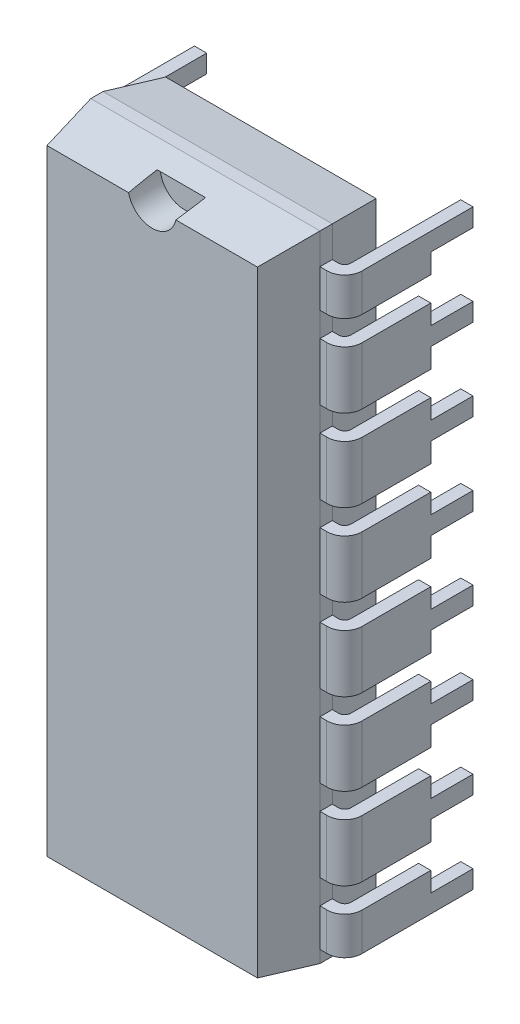
SolidWorks part; units mm, degrees
ref_plane "Спереди" through (0, 0, 0) normal (0, 0, 1) x (1, 0, 0)
ref_plane "Сверху" through (0, 0, 0) normal (0, 1, 0) x (1, 0, 0)
ref_plane "Справа" through (0, 0, 0) normal (1, 0, 0) x (0, 0, -1)
sketch "Эскиз1" plane through (0, 0, 0) normal (0, 0, 1) x (1, 0, 0)
  line L1 (-0.19, 0.28) -> (0.19, 0.28)
  line L2 (-0.19, 0.28) -> (-0.19, -0.89)
  line L3 (-0.19, -0.89) -> (0.19, -0.89)
  line L4 (0.19, 0.28) -> (0.19, -0.89)
  line L8 (-0.19, -1.65) -> (0.19, -1.65)
  line L9 (-0.19, -1.65) -> (-0.19, -3.43)
  line L10 (-0.19, -3.43) -> (0.19, -3.43)
  line L11 (0.19, -1.65) -> (0.19, -3.43)
  line L16 (-0.19, -4.19) -> (0.19, -4.19)
  line L17 (-0.19, -4.19) -> (-0.19, -5.97)
  line L18 (-0.19, -5.97) -> (0.19, -5.97)
  line L19 (0.19, -4.19) -> (0.19, -5.97)
  line L24 (-0.19, -6.73) -> (0.19, -6.73)
  line L25 (-0.19, -6.73) -> (-0.19, -8.51)
  line L26 (-0.19, -8.51) -> (0.19, -8.51)
  line L27 (0.19, -6.73) -> (0.19, -8.51)
  line L32 (-0.19, -9.27) -> (0.19, -9.27)
  line L33 (-0.19, -9.27) -> (-0.19, -11.05)
  line L34 (-0.19, -11.05) -> (0.19, -11.05)
  line L35 (0.19, -9.27) -> (0.19, -11.05)
  line L40 (-0.19, -11.81) -> (0.19, -11.81)
  line L41 (-0.19, -11.81) -> (-0.19, -13.59)
  line L42 (-0.19, -13.59) -> (0.19, -13.59)
  line L43 (0.19, -11.81) -> (0.19, -13.59)
  line L48 (-0.19, -14.35) -> (0.19, -14.35)
  line L49 (-0.19, -14.35) -> (-0.19, -16.13)
  line L50 (-0.19, -16.13) -> (0.19, -16.13)
  line L51 (0.19, -14.35) -> (0.19, -16.13)
  line L55 (-0.19, -16.89) -> (0.19, -16.89)
  line L57 (-0.19, -16.89) -> (-0.19, -18.06)
  line L58 (-0.19, -18.06) -> (0.19, -18.06)
  line L59 (0.19, -16.89) -> (0.19, -18.06)
ref_plane "Плоскость1" through (0, 0, 4.32) normal (0, 0, 1) x (1, 0, 0)
sketch "Эскиз2" plane through (0, 0, 4.32) normal (0, 0, 1) x (1, 0, 0)
  line L0 (4.13, 1.24) -> (4.13, -12.1874) construction
  line L1 (0.575, -8.6) -> (7.685, -8.6) construction
  line L7 (0.575, 1.24) -> (7.685, 1.24)
  line L8 (0.575, 1.24) -> (0.575, -18.44)
  line L9 (0.575, -18.44) -> (7.685, -18.44)
  line L10 (7.685, 1.24) -> (7.685, -18.44)
  dimension "D1" = 7.11
  dimension "D2" = 19.68
extrude "Вытянуть1" add sketch "Эскиз2" against normal blind 3.68
chamfer "Фаска1" distance 1.65 angle 10 8 edges at (4.13, -18.44, 0.64) (0.575, -8.6, 0.64) (4.13, 1.24, 0.64) (7.685, -8.6, 0.64) (4.13, -18.44, 4.32) (0.575, -8.6, 4.32) (4.13, 1.24, 4.32) (7.685, -8.6, 4.32)
sketch "Эскиз3" plane through (0, 0, 0) normal (0, 1, 0) x (1, 0, 0)
  line L0 (0, 0) -> (0, -2.1333)
  line L1 (0.3729, -2.4825) -> (4.1327, -2.4825)
  line L3 (4.13, -0.0853) -> (4.13, -2.9789) construction
  line L5 (7.8871, -2.4825) -> (4.1327, -2.4825)
  line L6 (8.26, 0) -> (8.26, -2.1333)
  arc A0 (0, -2.1333) -> (0.3729, -2.4825) centre (0.35, -2.1333) ccw
  arc A1 (8.26, -2.1333) -> (7.8871, -2.4825) centre (7.91, -2.1333) cw
  dimension "D2" = 0.35
  dimension "D1" = 8.26
  dimension "D3" = 2.4825
sweep "По траектории3" add profiles "Эскиз1" path "Эскиз3"
sketch "Эскиз4" plane through (0, 0, 0) normal (0, 0, 1) x (1, 0, 0)
  line L1 (8.07, 0.28) -> (8.45, 0.28)
  line L2 (8.07, 0.28) -> (8.07, -0.89)
  line L3 (8.07, -0.89) -> (8.45, -0.89)
  line L4 (8.45, 0.28) -> (8.45, -0.89)
  line L5 (8.07, -16.89) -> (8.45, -16.89)
  line L6 (8.07, -16.89) -> (8.07, -18.06)
  line L7 (8.07, -18.06) -> (8.45, -18.06)
  line L8 (8.45, -16.89) -> (8.45, -18.06)
  line L9 (8.07, -1.65) -> (8.45, -1.65)
  line L10 (8.07, -1.65) -> (8.07, -3.43)
  line L11 (8.07, -3.43) -> (8.45, -3.43)
  line L12 (8.45, -1.65) -> (8.45, -3.43)
  line L13 (8.07, -4.19) -> (8.45, -4.19)
  line L14 (8.07, -4.19) -> (8.07, -5.97)
  line L15 (8.07, -5.97) -> (8.45, -5.97)
  line L16 (8.45, -4.19) -> (8.45, -5.97)
  line L17 (8.07, -6.73) -> (8.45, -6.73)
  line L18 (8.07, -6.73) -> (8.07, -8.51)
  line L19 (8.07, -8.51) -> (8.45, -8.51)
  line L20 (8.45, -6.73) -> (8.45, -8.51)
  line L21 (8.07, -9.27) -> (8.45, -9.27)
  line L22 (8.07, -9.27) -> (8.07, -11.05)
  line L23 (8.07, -11.05) -> (8.45, -11.05)
  line L24 (8.45, -9.27) -> (8.45, -11.05)
  line L25 (8.07, -11.81) -> (8.45, -11.81)
  line L26 (8.07, -11.81) -> (8.07, -13.59)
  line L27 (8.07, -13.59) -> (8.45, -13.59)
  line L28 (8.45, -11.81) -> (8.45, -13.59)
  line L29 (8.07, -14.35) -> (8.45, -14.35)
  line L30 (8.07, -14.35) -> (8.07, -16.13)
  line L31 (8.07, -16.13) -> (8.45, -16.13)
  line L32 (8.45, -14.35) -> (8.45, -16.13)
sketch "Эскиз5" plane through (0, 0, 0) normal (0, 1, 0) x (1, 0, 0)
  line L0 (7.685, -2.48) -> (7.8737, -2.48)
  line L1 (7.685, -2.29) -> (7.685, -2.67) construction
  line L2 (8.26, -2.0937) -> (8.26, 0)
  line L3 (8.07, 0) -> (8.45, 0) construction
  arc A0 (7.8737, -2.48) -> (8.26, -2.0937) centre (7.8737, -2.0937) ccw
sweep "По траектории4" add profiles "Эскиз4" path "Эскиз5"
sketch "Эскиз6" plane through (0, 0, 4.32) normal (0, 0, 1) x (1, 0, 0)
  line L2 (3.38, 1.1079) -> (4.88, 1.1079)
  arc A1 (3.38, 1.1079) -> (4.88, 1.1079) centre (4.13, 1.1079) ccw
extrude "Вырез-Вытянуть1" cut sketch "Эскиз6" against normal blind 1
sketch "Эскиз7" plane through (0, 0, 0) normal (0, 0, 1) x (1, 0, 0)
  line L1 (0.19, 0.28) -> (-0.19, 0.28)
  line L2 (0.19, 0.28) -> (0.19, -0.28)
  line L3 (0.19, -0.28) -> (-0.19, -0.28)
  line L4 (-0.19, 0.28) -> (-0.19, -0.28)
  line L5 (0.19, -2.26) -> (-0.19, -2.26)
  line L6 (0.19, -2.26) -> (0.19, -2.82)
  line L7 (0.19, -2.82) -> (-0.19, -2.82)
  line L8 (-0.19, -2.26) -> (-0.19, -2.82)
  line L9 (0.19, -4.8) -> (-0.19, -4.8)
  line L10 (0.19, -4.8) -> (0.19, -5.36)
  line L11 (0.19, -5.36) -> (-0.19, -5.36)
  line L12 (-0.19, -4.8) -> (-0.19, -5.36)
  line L13 (0.19, -7.34) -> (-0.19, -7.34)
  line L14 (0.19, -7.34) -> (0.19, -7.9)
  line L15 (0.19, -7.9) -> (-0.19, -7.9)
  line L16 (-0.19, -7.34) -> (-0.19, -7.9)
  line L17 (0.19, -9.88) -> (-0.19, -9.88)
  line L18 (0.19, -9.88) -> (0.19, -10.44)
  line L19 (0.19, -10.44) -> (-0.19, -10.44)
  line L20 (-0.19, -9.88) -> (-0.19, -10.44)
  line L21 (0.19, -12.42) -> (-0.19, -12.42)
  line L22 (0.19, -12.42) -> (0.19, -12.98)
  line L23 (0.19, -12.98) -> (-0.19, -12.98)
  line L24 (-0.19, -12.42) -> (-0.19, -12.98)
  line L25 (0.19, -14.96) -> (-0.19, -14.96)
  line L26 (0.19, -14.96) -> (0.19, -15.52)
  line L27 (0.19, -15.52) -> (-0.19, -15.52)
  line L28 (-0.19, -14.96) -> (-0.19, -15.52)
  line L29 (0.19, -17.5) -> (-0.19, -17.5)
  line L30 (0.19, -17.5) -> (0.19, -18.06)
  line L31 (0.19, -18.06) -> (-0.19, -18.06)
  line L32 (-0.19, -17.5) -> (-0.19, -18.06)
  line L33 (8.45, 0.28) -> (8.07, 0.28)
  line L34 (8.45, 0.28) -> (8.45, -0.28)
  line L35 (8.45, -0.28) -> (8.07, -0.28)
  line L36 (8.07, 0.28) -> (8.07, -0.28)
  line L37 (8.45, -2.26) -> (8.07, -2.26)
  line L38 (8.45, -2.26) -> (8.45, -2.82)
  line L39 (8.45, -2.82) -> (8.07, -2.82)
  line L40 (8.07, -2.26) -> (8.07, -2.82)
  line L41 (8.45, -4.8) -> (8.07, -4.8)
  line L42 (8.45, -4.8) -> (8.45, -5.36)
  line L43 (8.45, -5.36) -> (8.07, -5.36)
  line L44 (8.07, -4.8) -> (8.07, -5.36)
  line L45 (8.45, -7.34) -> (8.07, -7.34)
  line L46 (8.45, -7.34) -> (8.45, -7.9)
  line L47 (8.45, -7.9) -> (8.07, -7.9)
  line L48 (8.07, -7.34) -> (8.07, -7.9)
  line L49 (8.45, -9.88) -> (8.07, -9.88)
  line L50 (8.45, -9.88) -> (8.45, -10.44)
  line L51 (8.45, -10.44) -> (8.07, -10.44)
  line L52 (8.07, -9.88) -> (8.07, -10.44)
  line L53 (8.45, -12.42) -> (8.07, -12.42)
  line L54 (8.45, -12.42) -> (8.45, -12.98)
  line L55 (8.45, -12.98) -> (8.07, -12.98)
  line L56 (8.07, -12.42) -> (8.07, -12.98)
  line L57 (8.45, -14.96) -> (8.07, -14.96)
  line L58 (8.45, -14.96) -> (8.45, -15.52)
  line L59 (8.45, -15.52) -> (8.07, -15.52)
  line L60 (8.07, -14.96) -> (8.07, -15.52)
  line L61 (8.45, -17.5) -> (8.07, -17.5)
  line L62 (8.45, -17.5) -> (8.45, -18.06)
  line L63 (8.45, -18.06) -> (8.07, -18.06)
  line L64 (8.07, -17.5) -> (8.07, -18.06)
  dimension "D1" = 0.28
  dimension "D2" = 0.56
  dimension "D3" = 0.19
  dimension "D4" = 0.38
  dimension "D5" = 2.54
  dimension "D6" = 8.26
extrude "Вытянуть2" add sketch "Эскиз7" against normal blind 3.81
sketch "Эскиз8" plane through (0, 0, -3.81) normal (0, 0, -1) x (-1, 0, 0)
  circle A0 centre (0, 0) radius 0.0866
extrude "Вырез-Вытянуть2" cut sketch "Эскиз8" against normal blind 3.5
sketch "Эскиз9" plane through (0, 0, -3.81) normal (0, 0, -1) x (-1, 0, 0)
  line L1 (-10.4881, -19.57) -> (2.049, -19.57)
  line L2 (-10.4881, -19.57) -> (-10.4881, 3.1162)
  line L3 (-10.4881, 3.1162) -> (2.049, 3.1162)
  line L4 (2.049, -19.57) -> (2.049, 3.1162)
extrude "Вырез-Вытянуть3" cut sketch "Эскиз9" against normal blind 2.5
